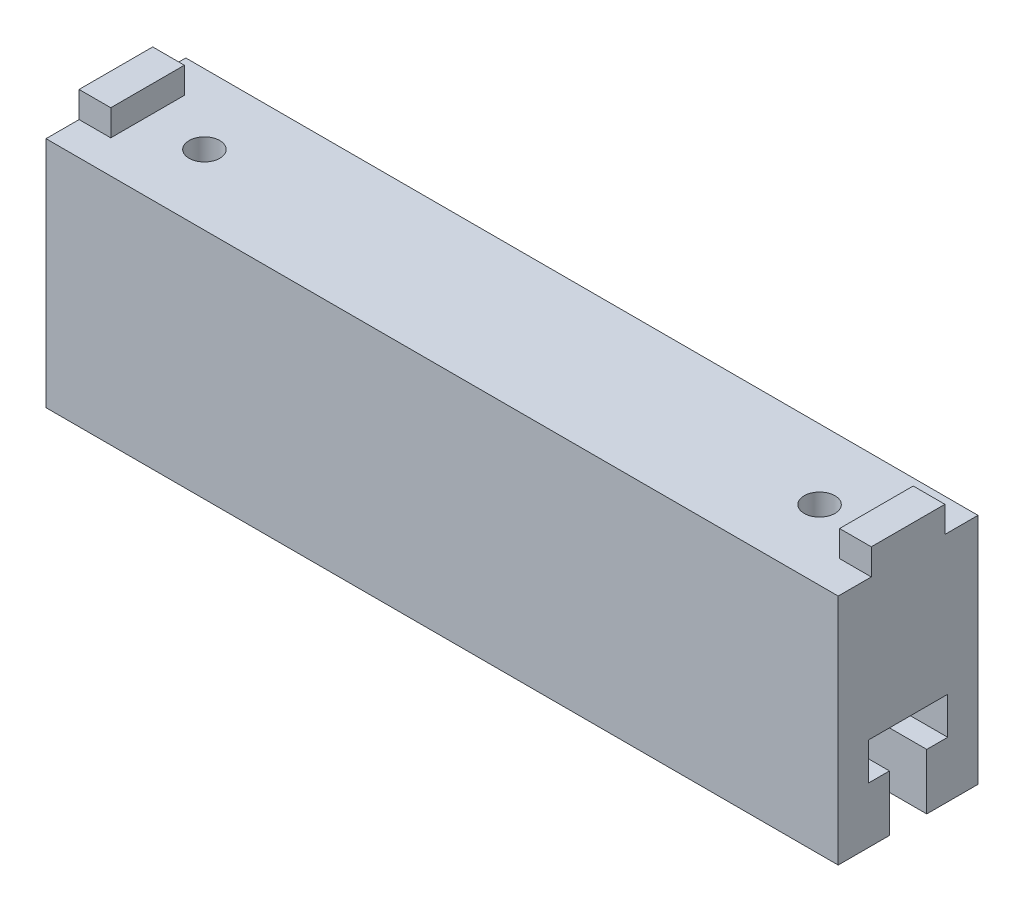
SolidWorks part; units mm, degrees
ref_plane "Front Plane" through (0, 0, 0) normal (0, 0, 1) x (1, 0, 0)
ref_plane "Top Plane" through (0, 0, 0) normal (0, 1, 0) x (1, 0, 0)
ref_plane "Right Plane" through (0, 0, 0) normal (1, 0, 0) x (0, 0, -1)
sketch "Sketch1" plane through (0, 0, 0) normal (0, 1, 0) x (1, 0, 0)
  line L1 (-42.5, -7.5) -> (42.5, -7.5)
  line L2 (-42.5, -7.5) -> (-42.5, 7.5)
  line L3 (-42.5, 7.5) -> (42.5, 7.5)
  line L4 (42.5, -7.5) -> (42.5, 7.5)
  line L5 (0, 7.5) -> (0, -7.5) construction
  line L6 (-42.5, 0) -> (42.5, 0) construction
  point P0 (0, 0)
  dimension "D1" = 15
  dimension "D2" = 85
extrude "Boss-Extrude1" add sketch "Sketch1" along normal blind 25
sketch "Sketch2" plane through (0, 25, 0) normal (0, 1, 0) x (1, 0, 0)
  line L0 (-42.5, 0) -> (42.5, 0) construction
  line L1 (-42.5, 7.5) -> (-42.5, -7.5) construction
  line L2 (42.5, -7.5) -> (42.5, 7.5) construction
  line L3 (0, 0) -> (0, 7.5) construction
  line L4 (-42.5, -3.95) -> (-39.1, -3.95)
  line L5 (-42.5, -3.95) -> (-42.5, 3.95)
  line L6 (-42.5, 3.95) -> (-39.1, 3.95)
  line L7 (-39.1, -3.95) -> (-39.1, 3.95)
  line L8 (42.5, 7.5) -> (-42.5, 7.5) construction
  line L9 (42.5, 3.95) -> (39.1, 3.95)
  line L10 (39.1, -3.95) -> (39.1, 3.95)
  line L11 (42.5, -3.95) -> (39.1, -3.95)
  line L12 (42.5, -3.95) -> (42.5, 3.95)
  point P10 (-42.5, 0)
  dimension "D1" = 7.9
  dimension "D2" = 3.4
extrude "Boss-Extrude2" add sketch "Sketch2" along normal blind 2.8
sketch "Sketch3" plane through (42.5, 0, 0) normal (1, 0, 0) x (0, 0, -1)
  line L0 (-7.5, 0) -> (7.5, 0) construction
  line L1 (-2, 0) -> (2, 0)
  line L2 (-2, 0) -> (-2, 6)
  line L4 (2, 0) -> (2, 6)
  line L6 (-4.25, 10) -> (4.25, 10)
  line L7 (-4.25, 10) -> (-4.25, 6)
  line L8 (-4.25, 6) -> (-2, 6)
  line L9 (4.25, 10) -> (4.25, 6)
  line L12 (2, 6) -> (4.25, 6)
  line L14 (0, 10) -> (0, 0) construction
  point P11 (0, 0)
  point P12 (0, 0)
  dimension "D1" = 6
  dimension "D2" = 4
  dimension "D3" = 4
  dimension "D5" = 8.5
extrude "Cut-Extrude2" cut sketch "Sketch3" against normal through all and the other way through all
sketch "Sketch5" plane through (0, 25, 0) normal (0, 1, 0) x (1, 0, 0)
  line L0 (0, 0) -> (-42.8274, 0) construction
  line L1 (0, 0) -> (0, -7.5) construction
  line L2 (-42.5, -7.5) -> (42.5, -7.5) construction
  circle A0 centre (33, 0) radius 1.651
  circle A1 centre (-33, 0) radius 1.651
  dimension "D2" = 3.302
  dimension "D1" = 33
extrude "Cut-Extrude3" cut sketch "Sketch5" against normal blind 9.525
